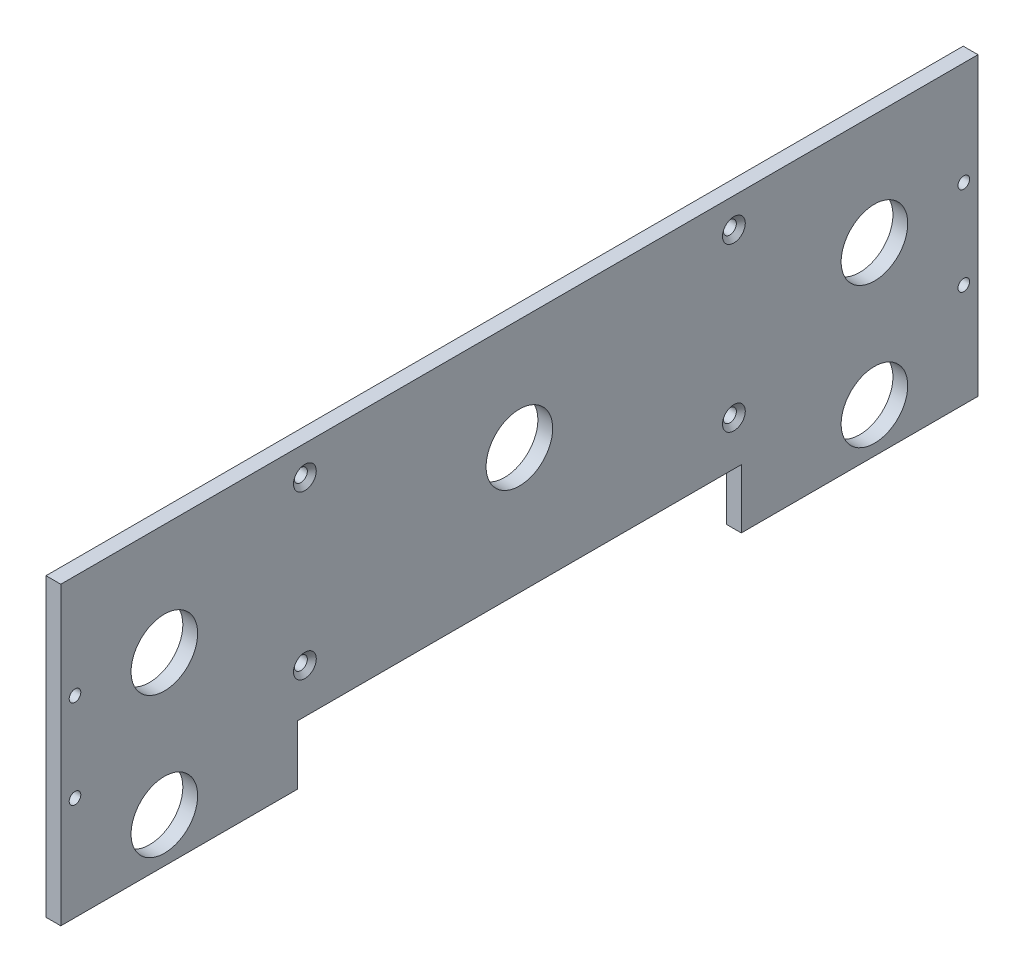
SolidWorks part; units mm, degrees
material "6061-T6 (SS)"
ref_plane "Front Plane" through (0, 0, 0) normal (0, 0, 1) x (1, 0, 0)
ref_plane "Top Plane" through (0, 0, 0) normal (0, 1, 0) x (1, 0, 0)
ref_plane "Right Plane" through (0, 0, 0) normal (1, 0, 0) x (0, 0, -1)
sketch "Sketch1" plane through (0, 0, 0) normal (1, 0, 0) x (0, 0, -1)
  line L1 (-196.85, 63.5) -> (196.85, 63.5)
  line L2 (-196.85, 63.5) -> (-196.85, -63.5)
  line L3 (-196.85, -63.5) -> (196.85, -63.5)
  line L4 (196.85, 63.5) -> (196.85, -63.5)
  line L5 (-196.85, 63.5) -> (196.85, -63.5) construction
  line L6 (-196.85, -63.5) -> (196.85, 63.5) construction
  point P0 (0, 0)
  dimension "D1" = 127
  dimension "D2" = 393.7
extrude "Boss-Extrude1" add sketch "Sketch1" along normal blind 6.35
sketch "Sketch2" plane through (6.35, 0, 0) normal (1, 0, 0) x (0, 0, -1)
  line L0 (-196.85, -63.5) -> (196.85, -63.5) construction
  line L1 (-152.4, 15.875) -> (0, 15.875) construction
  line L2 (-76.2, -34.925) -> (-76.2, 15.875) construction
  line L3 (0, 15.875) -> (152.4, 15.875) construction
  line L4 (76.2, -34.925) -> (76.2, 15.875) construction
  line L5 (196.85, 63.5) -> (-196.85, 63.5) construction
  line L6 (65.278, 53.34) -> (-56.642, 53.34) construction
  line L7 (65.278, 53.34) -> (65.278, -13.97) construction
  line L8 (65.278, -13.97) -> (-56.642, -13.97) construction
  line L9 (-56.642, 53.34) -> (-56.642, -13.97) construction
  line L10 (-196.85, -63.5) -> (196.85, -63.5) construction
  circle A0 centre (0, 15.875) radius 14.2875
  circle A1 centre (-152.4, 15.875) radius 14.2875
  circle A2 centre (152.4, 15.875) radius 14.2875
  circle A3 centre (-152.4, 15.875) radius 38.1 construction
  circle A4 centre (0, 15.875) radius 38.1 construction
  circle A5 centre (152.4, 15.875) radius 38.1 construction
  circle A6 centre (-76.2, -34.925) radius 6.35 construction
  circle A7 centre (76.2, -34.925) radius 6.35 construction
  circle A8 centre (-76.2, 9.525) radius 6.35 construction
  circle A9 centre (76.2, 9.525) radius 6.35 construction
  circle A11 centre (-152.4, -44.45) radius 14.2875
  circle A12 centre (152.4, -44.45) radius 14.2875
  point P11 (0, 0)
  dimension "D1" = 28.575
  dimension "D5" = 76.2
  dimension "D7" = 12.7
  dimension "D14" = 28.575
  dimension "D15" = 19.05
  dimension "D17" = 28.575
  dimension "D2" = 79.375
  dimension "D3" = 152.4
  dimension "D4" = 152.4
  dimension "D6" = 0
  dimension "D8" = 28.575
  dimension "D9" = 44.45
  dimension "D10" = 56.642
  dimension "D11" = 121.92
  dimension "D12" = 10.16
  dimension "D13" = 49.53
  dimension "D16" = 152.4
  dimension "D18" = 19.05
  dimension "D19" = 152.4
extrude "Cut-Extrude1" cut sketch "Sketch2" against normal through all
sketch "Sketch3" plane through (6.35, 0, 0) normal (1, 0, 0) x (0, 0, -1)
  line L0 (-190.754, 19.05) -> (-190.754, -19.05) construction
  line L1 (-196.85, 63.5) -> (-196.85, -63.5) construction
  point P2 (-190.754, 0)
  point P3 (-196.85, 0)
  dimension "D1" = 38.1
  dimension "D2" = 6.096
hole_wizard "#10 Clearance Hole1" positions "Sketch4" profile "Sketch6" hole size "#10" standard "ANSI Inch" end condition through all
sketch "Sketch4" plane through (6.35, 0, 0) normal (1, 0, 0) x (0, 0, -1)
  line L3 (196.85, -63.5) -> (196.85, 63.5) construction
  point P0 (-190.754, 19.05)
  point P3 (-190.754, -19.05)
  point P8 (190.754, 19.05)
  point P10 (190.754, -19.05)
  dimension "D1" = 6.096
  dimension "D2" = 6.096
sketch "Sketch6" plane through (6.35, 19.05, 190.754) normal (0, 1, 0) x (0, 0, -1)
  line L0 (0, 0) -> (0, 6.35)
  line L1 (0, 6.35) -> (2.4892, 6.35)
  line L2 (2.4892, 6.35) -> (2.4892, 0)
  line L5 (2.4892, 0) -> (0, 0)
  line L11 (0, -6.35) -> (0, 107.95) construction
  dimension "Thru Hole Dia." = 4.9784
  dimension "Thru Hole Depth" = 6.35
hole_wizard "CSK for #10 Flat Head Machine Screw (100)1" positions "Sketch7" profile "Sketch8" countersink size "#10" standard "ANSI Inch" end condition through all
sketch "Sketch7" plane through (6.35, 0, 0) normal (1, 0, 0) x (0, 0, -1)
  line L1 (196.85, 63.5) -> (-196.85, 63.5) construction
  point P15 (-92.075, 50.8)
  point P17 (92.075, 50.8)
  point P19 (-92.075, -19.05)
  point P21 (92.075, -19.05)
  dimension "D1" = 12.7
  dimension "D2" = 12.7
  dimension "D3" = 69.85
  dimension "D4" = 69.85
sketch "Sketch8" plane through (6.35, 50.8, 92.075) normal (0, 1, 0) x (0, 0, -1)
  line L0 (0, 0) -> (0, 6.35)
  line L1 (0, 6.35) -> (2.8067, 6.35)
  line L2 (2.8067, 6.35) -> (2.8067, 1.7477)
  line L3 (2.8067, 1.7477) -> (4.8895, 0)
  line L5 (4.8895, 0) -> (0, 0)
  line L6 (-2.8067, 1.7477) -> (-4.8895, 0) construction
  line L11 (0, -6.35) -> (0, 107.95) construction
  dimension "Thru Hole Dia." = 5.6134
  dimension "Thru Hole Depth" = 6.35
  dimension "Near C'Sink Dia." = 9.779
  dimension "Near C'Sink Angle" = 100
sketch "Sketch23" plane through (6.35, 0, 0) normal (1, 0, 0) x (0, 0, -1)
  line L0 (-95.25, -63.5) -> (-95.25, -38.1)
  line L1 (-196.85, -63.5) -> (196.85, -63.5) construction
  line L2 (-95.25, -38.1) -> (95.25, -38.1)
  line L3 (95.25, -38.1) -> (95.25, -63.5)
  line L4 (-196.85, 63.5) -> (-196.85, -63.5) construction
  line L5 (196.85, -63.5) -> (196.85, 63.5) construction
  line L6 (-95.25, -63.5) -> (95.25, -63.5)
  dimension "D1" = 25.4
  dimension "D2" = 101.6
  dimension "D3" = 101.6
extrude "Cut-Extrude6" cut sketch "Sketch23" against normal through all
